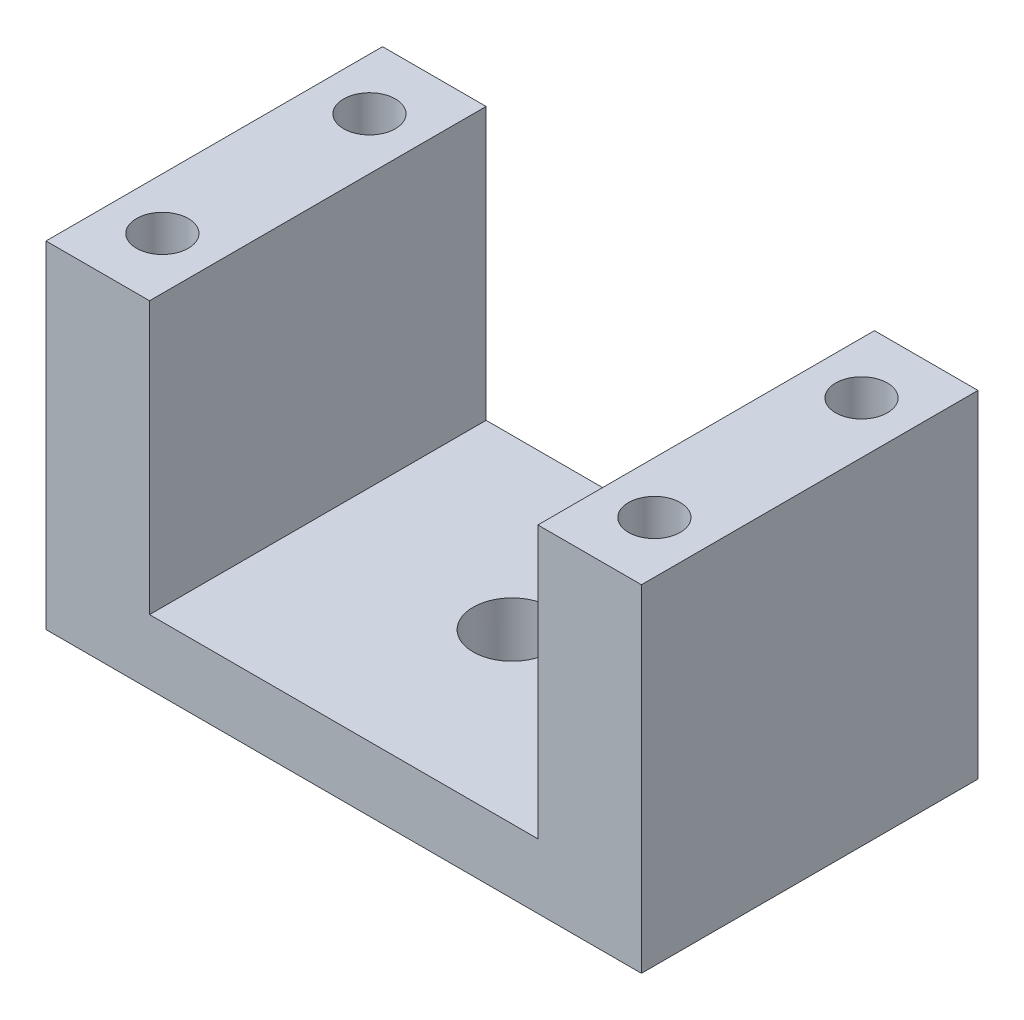
SolidWorks part; units mm, degrees
material "普通碳钢"
ref_plane "前视基准面" through (0, 0, 0) normal (0, 0, 1) x (1, 0, 0)
ref_plane "上视基准面" through (0, 0, 0) normal (0, 1, 0) x (1, 0, 0)
ref_plane "右视基准面" through (0, 0, 0) normal (1, 0, 0) x (0, 0, -1)
sketch "草图1" plane through (0, 0, 0) normal (0, 0, 1) x (1, 0, 0)
  line L0 (-7.5, 6.5) -> (-7.5, -4)
  line L5 (-11.5, 6.5) -> (-7.5, 6.5)
  line L6 (-11.5, 6.5) -> (-11.5, -6.5)
  line L11 (-11.5, -6.5) -> (11.5, -6.5)
  line L12 (11.5, 6.5) -> (11.5, -6.5)
  line L13 (-11.5, 6.5) -> (11.5, -6.5) construction
  line L14 (-11.5, -6.5) -> (11.5, 6.5) construction
  line L15 (-7.5, -4) -> (7.5, -4)
  line L16 (7.5, -4) -> (7.5, 6.5)
  line L17 (7.5, 6.5) -> (11.5, 6.5)
  point P0 (0, 0)
  dimension "D1" = 13
  dimension "D2" = 23
  dimension "D3" = 10.5
  dimension "D4" = 15
  dimension "D5" = 4
extrude "凸台-拉伸1" add sketch "草图1" along normal blind 13
sketch "草图2" plane through (0, 6.5, 0) normal (0, 1, 0) x (1, 0, 0)
  line L0 (-7.5, 0) -> (-11.5, 0) construction
  line L1 (-7.5, -13) -> (-11.5, -13) construction
  line L2 (-7.5, -13) -> (-7.5, 0) construction
  line L3 (11.5, -13) -> (7.5, -13) construction
  line L4 (11.5, 0) -> (7.5, 0) construction
  line L5 (11.5, -13) -> (11.5, 0) construction
  line L6 (7.5, -13) -> (-7.5, -13) construction
  line L7 (7.5, -13) -> (7.5, 0) construction
  circle A0 centre (-9.5049, -2.5) radius 1
  circle A1 centre (-9.5049, -10.5) radius 1
  circle A2 centre (9.5, -2.5) radius 1
  circle A3 centre (9.5, -10.5) radius 1
  circle A4 centre (0, -6.5) radius 1.5
  dimension "D1" = 2
  dimension "D2" = 2
  dimension "D3" = 2
  dimension "D4" = 2
  dimension "D5" = 8
  dimension "D6" = 2.5
  dimension "D7" = 2.5
  dimension "D8" = 2.0049
  dimension "D9" = 2.5
  dimension "D10" = 8
  dimension "D11" = 2.5
  dimension "D12" = 2
  dimension "D13" = 3
  dimension "D14" = 6.5
  dimension "D15" = 7.5
extrude "切除-拉伸1" cut sketch "草图2" against normal through all
